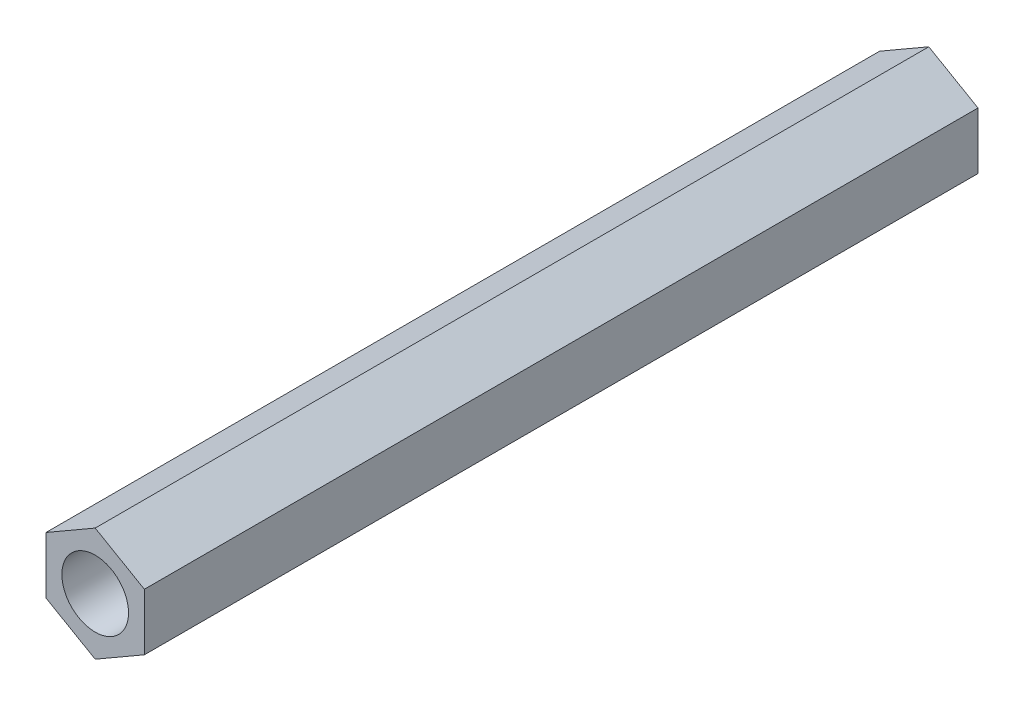
SolidWorks part; units mm, degrees
ref_plane "前视基准面" through (0, 0, 0) normal (0, 0, 1) x (1, 0, 0)
ref_plane "上视基准面" through (0, 0, 0) normal (0, 1, 0) x (1, 0, 0)
ref_plane "右视基准面" through (0, 0, 0) normal (1, 0, 0) x (0, 0, -1)
other "Configuration Table"
sketch "草图1" plane through (0, 0, 0) normal (0, 0, 1) x (1, 0, 0)
  line L1 (2.95, -1.7032) -> (2.95, 1.7032)
  line L2 (2.95, 1.7032) -> (0, 3.4064)
  line L3 (0, 3.4064) -> (-2.95, 1.7032)
  line L4 (-2.95, 1.7032) -> (-2.95, -1.7032)
  line L5 (-2.95, -1.7032) -> (0, -3.4064)
  line L6 (0, -3.4064) -> (2.95, -1.7032)
  circle A0 centre (0, 0) radius 2.95 construction
  circle A1 centre (0, 0) radius 2
  dimension "D2" = 4
  dimension "D1" = 5.9
extrude "凸台-拉伸1" add sketch "草图1" along normal blind 50
